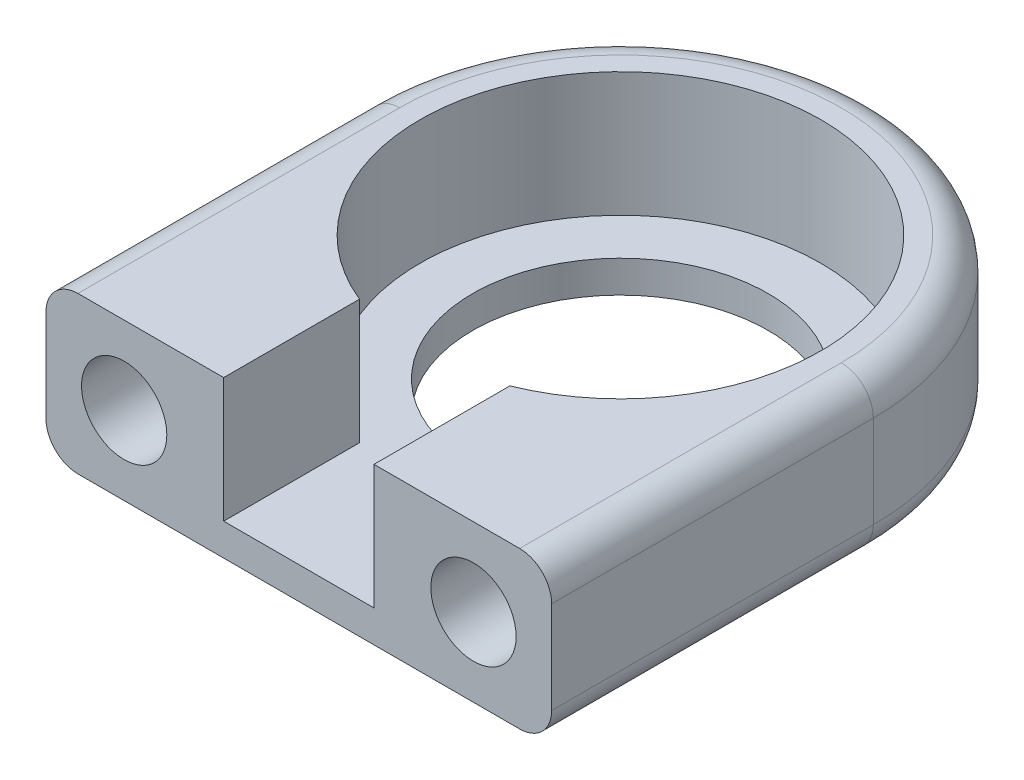
SolidWorks part; units mm, degrees
material "6061-T6 (SS)"
ref_plane "Front Plane" through (0, 0, 0) normal (0, 0, 1) x (1, 0, 0)
ref_plane "Top Plane" through (0, 0, 0) normal (0, 1, 0) x (1, 0, 0)
ref_plane "Right Plane" through (0, 0, 0) normal (1, 0, 0) x (0, 0, -1)
sketch "Sketch1" plane through (0, 0, 0) normal (0, 1, 0) x (1, 0, 0)
  line L0 (-17.7875, -22.6281) -> (17.7875, -22.6281)
  line L31 (-17.7875, 0) -> (-17.7875, -22.6281)
  line L32 (17.7875, 0) -> (17.7875, -22.6281)
  circle A2 centre (0, 0) radius 14.0975
  arc A4 (17.7875, 0) -> (-17.7875, 0) centre (0, 0) ccw
  circle A5 centre (0, 0) radius 17.7875 construction
  point P3 (0, -14.2875)
  dimension "D1" = 3.69
extrude "Boss-Extrude1" add sketch "Sketch1" along normal blind 11
sketch "Sketch3" plane through (0, 11, 0) normal (0, 1, 0) x (1, 0, 0)
  line L17 (17.7875, -22.6281) -> (5.2875, -22.6281) construction
  line L21 (-17.7875, -22.6281) -> (17.7875, -22.6281) construction
  line L23 (-17.7875, -22.6281) -> (-5.2875, -22.6281) construction
  line L25 (-5.2875, -22.6281) -> (5.2875, -22.6281)
  line L26 (5.2875, -22.6281) -> (5.2875, -10.3998)
  line L27 (5.2875, -10.3998) -> (-5.2875, -10.3998)
  line L28 (-5.2875, -10.3998) -> (-5.2875, -22.6281)
sketch "Sketch4" plane through (0, 0, 0) normal (0, -1, 0) x (1, 0, 0)
  circle A0 centre (0, 0) radius 14.0975
extrude "Boss-Extrude2" add sketch "Sketch4" against normal blind 2.25
sketch "Sketch5" plane through (0, 2.25, 0) normal (0, 1, 0) x (1, 0, 0)
  circle A0 centre (0, 0) radius 10.4
extrude "Cut-Extrude1" cut sketch "Sketch5" against normal blind 2.25
extrude "Cut-Extrude5" cut sketch "Sketch3" against normal blind 8.75
sketch "Sketch6" plane through (0, 0, 22.6281) normal (0, 0, 1) x (1, 0, 0)
  line L0 (-17.7875, 5.5) -> (-12.2875, 5.5) construction
  line L1 (-17.7875, 11) -> (-17.7875, 0) construction
  line L2 (17.7875, 5.5) -> (12.2875, 5.5) construction
  line L3 (17.7875, 11) -> (17.7875, 0) construction
  circle A0 centre (-12.2875, 5.5) radius 3
  circle A1 centre (12.2875, 5.5) radius 3
extrude "Cut-Extrude6" cut sketch "Sketch6" against normal blind 9
fillet "Fillet5" radius 2.25 3 edges at (-17.7875, 0, 11.314) (0, 0, -17.7875) (17.7875, 0, 11.314)
fillet "Fillet6" radius 2.25 3 edges at (17.7875, 11, 11.314) (0, 11, -17.7875) (-17.7875, 11, 11.314)
